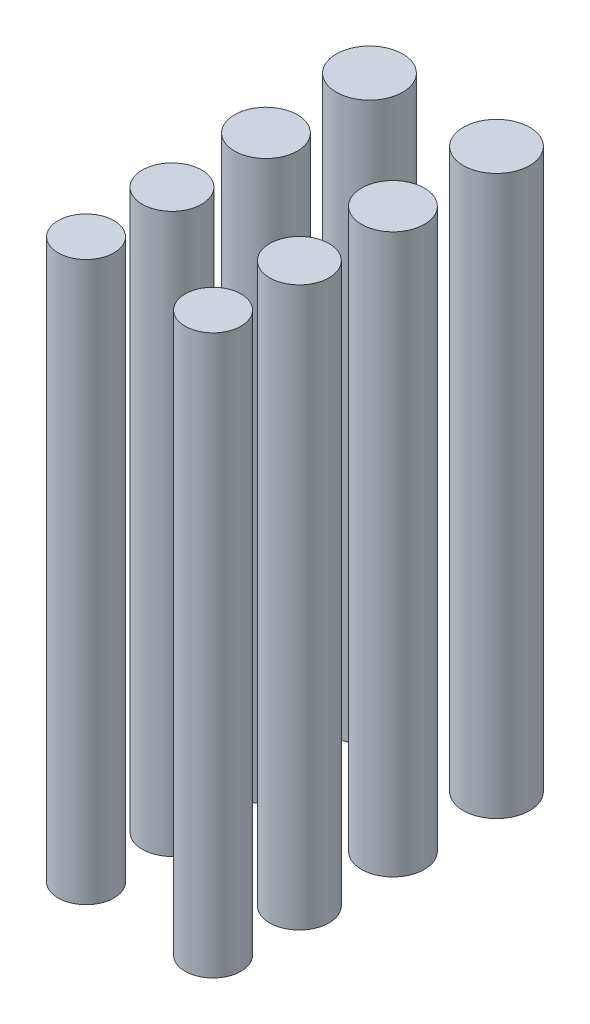
SolidWorks part; units mm, degrees
ref_plane "Front Plane" through (0, 0, 0) normal (0, 0, 1) x (1, 0, 0)
ref_plane "Top Plane" through (0, 0, 0) normal (0, 1, 0) x (1, 0, 0)
ref_plane "Right Plane" through (0, 0, 0) normal (1, 0, 0) x (0, 0, -1)
sketch "Sketch2" plane through (0, 0, 0) normal (0, 1, 0) x (1, 0, 0)
  circle A0 centre (-47.5331, 23.0838) radius 0.9
  circle A2 centre (-43.8963, 23.0838) radius 0.9
  circle A3 centre (-47.5331, 20.3928) radius 0.85
  circle A4 centre (-43.8853, 20.3928) radius 0.85
  circle A5 centre (-47.5331, 17.9321) radius 0.8
  circle A6 centre (-43.8963, 17.9321) radius 0.8
  circle A7 centre (-47.5331, 26.0497) radius 0.95
  circle A8 centre (-43.8963, 26.0497) radius 0.95
extrude "Boss-Extrude1" add sketch "Sketch2" along normal blind 16
